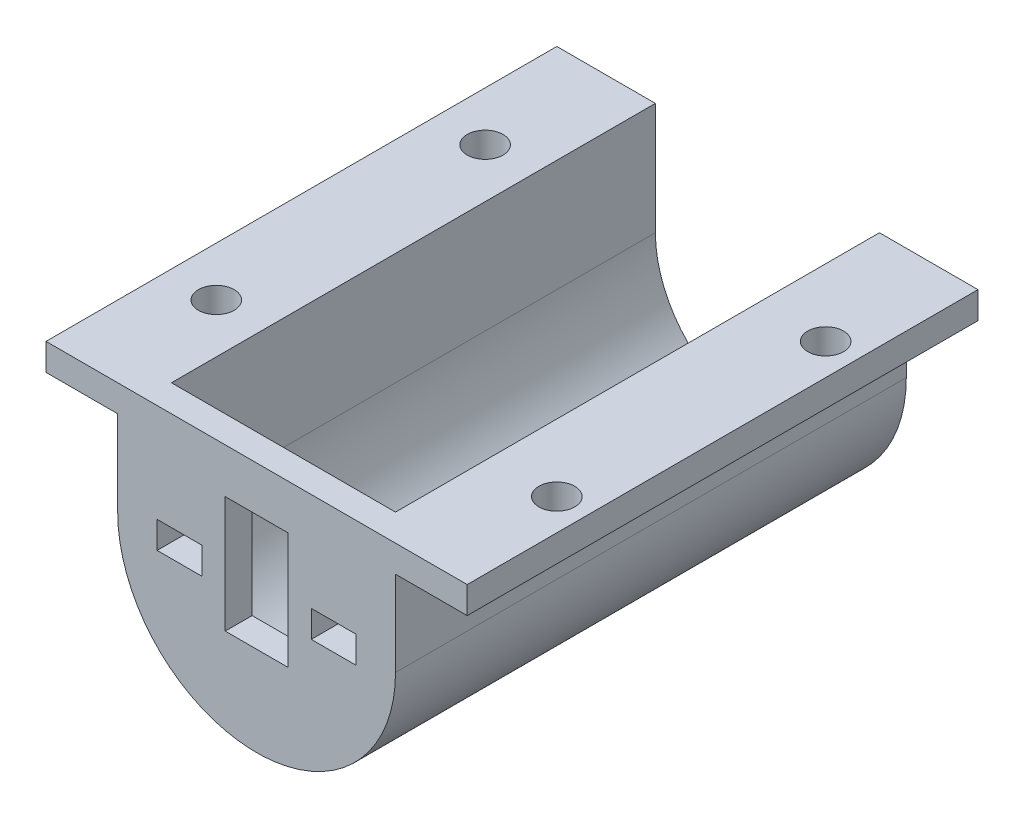
SolidWorks part; units mm, degrees
ref_plane "Alzado" through (0, 0, 0) normal (0, 0, 1) x (1, 0, 0)
ref_plane "Planta" through (0, 0, 0) normal (0, 1, 0) x (1, 0, 0)
ref_plane "Vista lateral" through (0, 0, 0) normal (1, 0, 0) x (0, 0, -1)
sketch "Croquis1" plane through (0, 0, 0) normal (0, 0, 1) x (1, 0, 0)
  line L4 (-12.5, 0) -> (-12.5, 12.5)
  line L13 (-12.5, 12.5) -> (-23.5, 12.5)
  line L14 (-23.5, 12.5) -> (-23.5, 9.5)
  line L15 (-23.5, 9.5) -> (-15.5, 9.5)
  line L16 (-15.5, 9.5) -> (-15.5, 0)
  line L17 (12.5, 0) -> (12.5, 12.5)
  line L18 (12.5, 12.5) -> (23.5, 12.5)
  line L19 (23.5, 12.5) -> (23.5, 9.5)
  line L20 (23.5, 9.5) -> (15.5, 9.5)
  line L21 (15.5, 9.5) -> (15.5, 0)
  line L22 (0, 12.5) -> (0, -12.5) construction
  line L23 (0, -15.5) -> (0, -12.5) construction
  arc A5 (-12.5, 0) -> (12.5, 0) centre (0, 0) ccw
  arc A6 (-15.5, 0) -> (15.5, 0) centre (0, 0) ccw
  dimension "D1" = 25
  dimension "D5" = 11
  dimension "D6" = 8
  dimension "D2" = 11
  dimension "D3" = 3
  dimension "D4" = 8
extrude "Saliente-Extruir1" add sketch "Croquis1" along normal mid plane 57
sketch "Croquis2" plane through (0, 9.5, 0) normal (0, -1, 0) x (1, 0, 0)
  line L0 (0, 0) -> (10.7106, 0) construction
  circle A0 centre (-18, 15) radius 2
  circle A1 centre (-18, -15) radius 2
  circle A2 centre (20, 15) radius 2
  circle A3 centre (20, -15) radius 2
  dimension "D1" = 4
  dimension "D3" = 16
  dimension "D4" = 18
  dimension "D2" = 15
  dimension "D5" = 15
extrude "Cortar-Extruir1" cut sketch "Croquis2" against normal blind 5
sketch "Croquis3" plane through (0, 0, 28.5) normal (0, 0, 1) x (1, 0, 0)
  line L0 (-12.5, 12.5) -> (-23.5, 12.5) construction
  line L1 (-15.5, 12.5) -> (15.5, 12.5)
  line L2 (-15.5, 12.5) -> (-15.5, 0)
  line L4 (15.5, 12.5) -> (15.5, 0)
  line L5 (-15.5, 9.5) -> (-15.5, 0) construction
  arc A0 (-15.5, 0) -> (15.5, 0) centre (0, 0) ccw construction
  arc A1 (-15.5, 0) -> (15.5, 0) centre (0, 0) ccw
extrude "Saliente-Extruir2" add sketch "Croquis3" against normal blind 3
sketch "Croquis4" plane through (0, 0, 28.5) normal (0, 0, 1) x (1, 0, 0)
  line L0 (0, 0) -> (0, -15.5) construction
  line L1 (-11.1, -1.5) -> (-6.1, -1.5)
  line L2 (23.5, 12.5) -> (-23.5, 12.5) construction
  line L3 (3.5, -5.5) -> (-3.5, -5.5)
  line L4 (11.1, 0) -> (-11.1, 0) construction
  line L6 (-3.5, -5.5) -> (-3.5, 7.5)
  line L7 (-3.5, 7.5) -> (3.5, 7.5)
  line L8 (3.5, -5.5) -> (3.5, 7.5)
  line L17 (11.1, 1.5) -> (6.1, 1.5)
  line L18 (11.1, 1.5) -> (11.1, -1.5)
  line L19 (11.1, -1.5) -> (6.1, -1.5)
  line L20 (6.1, 1.5) -> (6.1, -1.5)
  line L21 (-11.1, 1.5) -> (-11.1, -1.5)
  line L22 (-6.1, 1.5) -> (-6.1, -1.5)
  line L23 (-11.1, 1.5) -> (-6.1, 1.5)
  arc A2 (-15.5, 0) -> (15.5, 0) centre (0, 0) ccw construction
  dimension "D1" = 5
  dimension "D3" = 13
  dimension "D5" = 3
  dimension "D2" = 7
  dimension "D4" = 22.2
  dimension "D6" = 5
extrude "Cortar-Extruir3" cut sketch "Croquis4" against normal blind 3
